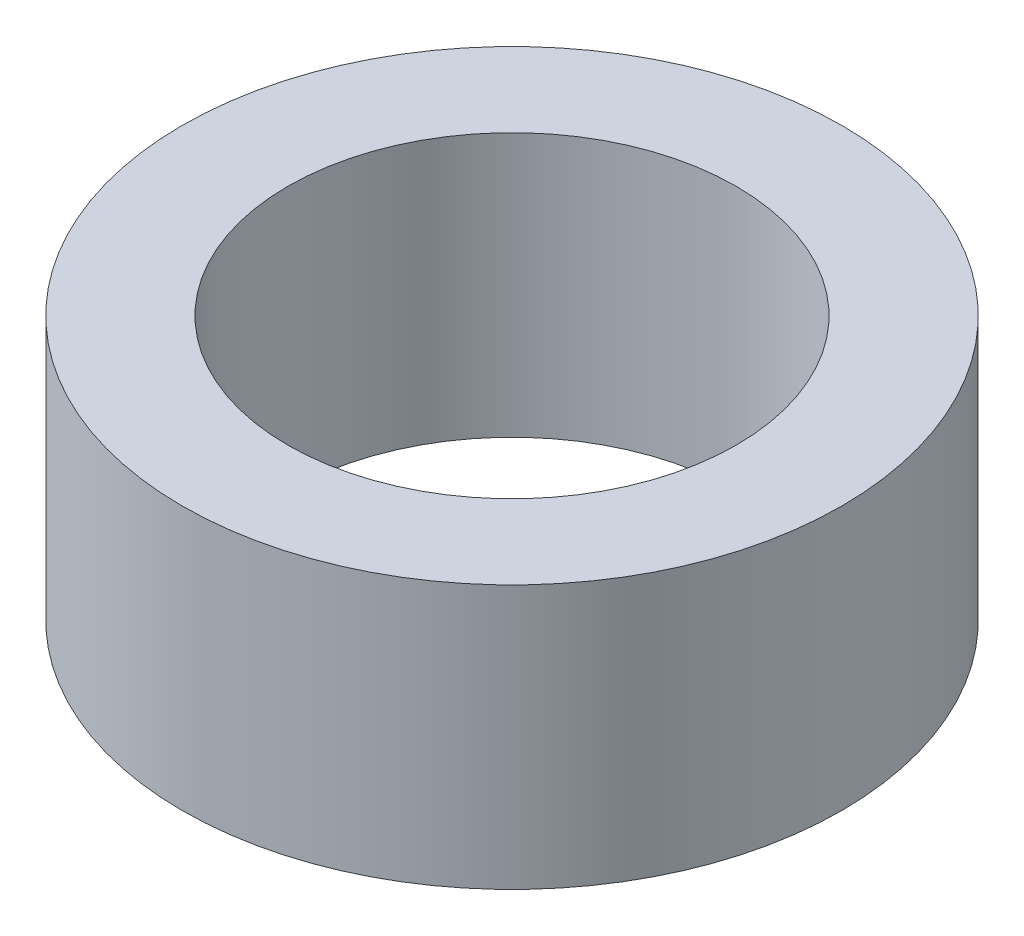
SolidWorks part; units mm, degrees
ref_plane "Front Plane" through (0, 0, 0) normal (0, 0, 1) x (1, 0, 0)
ref_plane "Top Plane" through (0, 0, 0) normal (0, 1, 0) x (1, 0, 0)
ref_plane "Right Plane" through (0, 0, 0) normal (1, 0, 0) x (0, 0, -1)
sketch "Sketch1" plane through (0, 0, 0) normal (0, 1, 0) x (1, 0, 0)
  circle A0 centre (0, 0) radius 4.25
  circle A1 centre (0, 0) radius 6.25
  dimension "D1" = 8.5
  dimension "D2" = 12.5
extrude "Boss-Extrude1" add sketch "Sketch1" along normal blind 5
